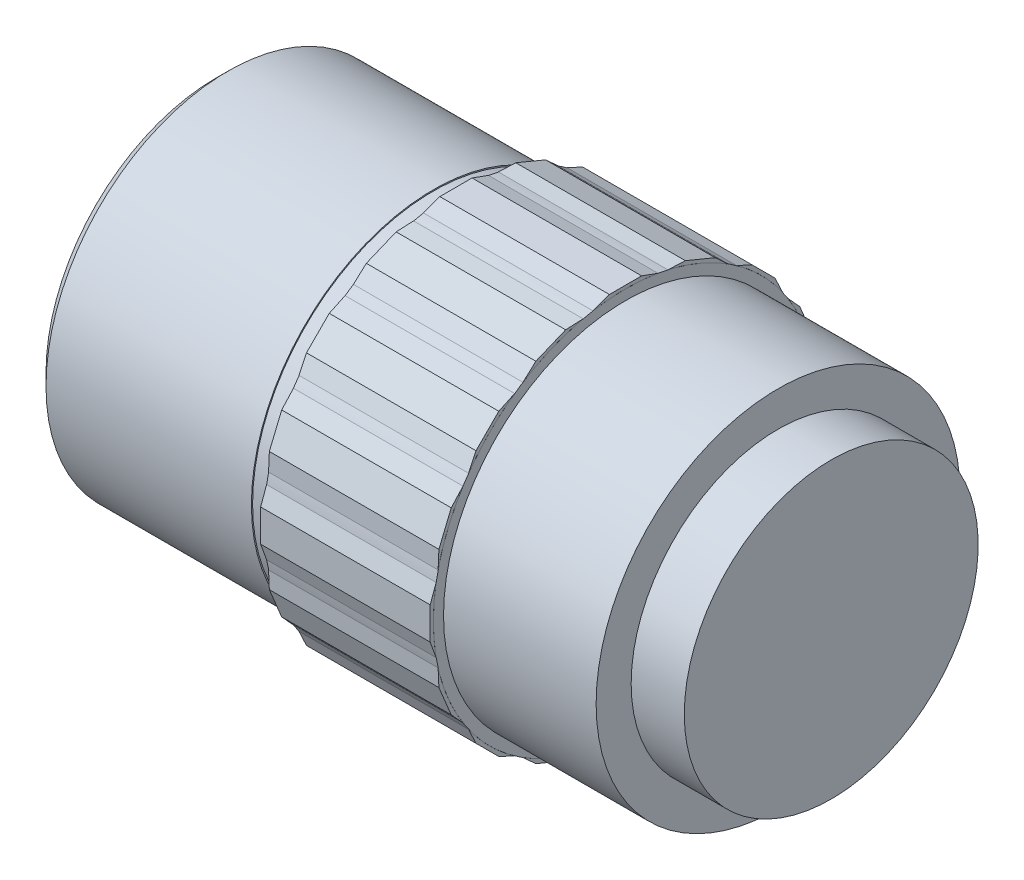
SolidWorks part; units mm, degrees
ref_plane "Front Plane" through (0, 0, 0) normal (0, 0, 1) x (1, 0, 0)
ref_plane "Top Plane" through (0, 0, 0) normal (0, 1, 0) x (1, 0, 0)
ref_plane "Right Plane" through (0, 0, 0) normal (1, 0, 0) x (0, 0, -1)
sketch "Sketch1" plane through (0, 0, 0) normal (0, 0, 1) x (1, 0, 0)
  line L0 (0, 0) -> (0, 13)
  line L1 (0, 13) -> (-4.7, 13)
  line L2 (-4.7, 13) -> (-4.7, 16.1)
  line L3 (-4.7, 16.1) -> (-18.2, 16.1)
  line L4 (-18.2, 16.1) -> (-18.2, 17)
  line L5 (-18.2, 17) -> (-33.2, 17)
  line L6 (-33.2, 17) -> (-33.2, 16.1)
  line L7 (-33.2, 16.1) -> (-53.3705, 16.1)
  line L8 (-53.3705, 16.1) -> (-54.4, 15.0705)
  line L9 (-54.4, 15.0705) -> (-54.4, 7.8723)
  line L10 (-54.4, 7.8723) -> (-54.7, 7.5723)
  line L11 (-54.7, 7.5723) -> (-54.7, 0)
  line L12 (-54.7, 0) -> (0, 0)
  point P8 (-18.2, 16.55)
  point P15 (-53.8057, 8.9982)
  point P16 (-53.664, 14.7558)
  point P17 (-53.9774, 16.1)
  dimension "D1" = 4.7
  dimension "D2" = 13.5
  dimension "D3" = 15
  dimension "D4" = 50
  dimension "D5" = 16.1
  dimension "D6" = 45
  dimension "D7" = 45
  dimension "D8" = 17
  dimension "D9" = 13
revolve "Revolve1" add sketch "Sketch1" angle 360 about L12
sketch "Sketch2" plane through (-33.2, 0, 0) normal (-1, 0, 0) x (0, 0, 1)
  line L0 (16.7543, 2.8797) -> (17.2804, 1.4257)
  line L1 (17.2804, 1.4257) -> (17.2804, -1.4257)
  line L2 (17.2804, -1.4257) -> (16.7543, -2.8797)
  line L3 (15.4194, -7.9301) -> (14.377, -9.0721)
  line L4 (16.5106, -5.2957) -> (15.4194, -7.9301)
  line L5 (16.581, -3.7511) -> (16.5106, -5.2957)
  line L6 (11.2109, -13.2272) -> (9.8108, -13.8833)
  line L7 (13.2272, -11.2109) -> (11.2109, -13.2272)
  line L8 (13.8833, -9.8108) -> (13.2272, -11.2109)
  line L9 (5.2957, -16.5106) -> (3.7511, -16.581)
  line L10 (7.9301, -15.4194) -> (5.2957, -16.5106)
  line L11 (9.0721, -14.377) -> (7.9301, -15.4194)
  line L12 (-1.4257, -17.2804) -> (-2.8797, -16.7543)
  line L13 (1.4257, -17.2804) -> (-1.4257, -17.2804)
  line L14 (2.8797, -16.7543) -> (1.4257, -17.2804)
  line L15 (-7.9301, -15.4194) -> (-9.0721, -14.377)
  line L16 (-5.2957, -16.5106) -> (-7.9301, -15.4194)
  line L17 (-3.7511, -16.581) -> (-5.2957, -16.5106)
  line L18 (-13.2272, -11.2109) -> (-13.8833, -9.8108)
  line L19 (-11.2109, -13.2272) -> (-13.2272, -11.2109)
  line L20 (-9.8108, -13.8833) -> (-11.2109, -13.2272)
  line L21 (-16.5106, -5.2957) -> (-16.581, -3.7511)
  line L22 (-15.4194, -7.9301) -> (-16.5106, -5.2957)
  line L23 (-14.377, -9.0721) -> (-15.4194, -7.9301)
  line L24 (-17.2804, 1.4257) -> (-16.7543, 2.8797)
  line L25 (-17.2804, -1.4257) -> (-17.2804, 1.4257)
  line L26 (-16.7543, -2.8797) -> (-17.2804, -1.4257)
  line L27 (-15.4194, 7.9301) -> (-14.377, 9.0721)
  line L28 (-16.5106, 5.2957) -> (-15.4194, 7.9301)
  line L29 (-16.581, 3.7511) -> (-16.5106, 5.2957)
  line L30 (-11.2109, 13.2272) -> (-9.8108, 13.8833)
  line L31 (-13.2272, 11.2109) -> (-11.2109, 13.2272)
  line L32 (-13.8833, 9.8108) -> (-13.2272, 11.2109)
  line L33 (-5.2957, 16.5106) -> (-3.7511, 16.581)
  line L34 (-7.9301, 15.4194) -> (-5.2957, 16.5106)
  line L35 (-9.0721, 14.377) -> (-7.9301, 15.4194)
  line L36 (1.4257, 17.2804) -> (2.8797, 16.7543)
  line L37 (-1.4257, 17.2804) -> (1.4257, 17.2804)
  line L38 (-2.8797, 16.7543) -> (-1.4257, 17.2804)
  line L39 (7.9301, 15.4194) -> (9.0721, 14.377)
  line L40 (5.2957, 16.5106) -> (7.9301, 15.4194)
  line L41 (3.7511, 16.581) -> (5.2957, 16.5106)
  line L42 (13.2272, 11.2109) -> (13.8833, 9.8108)
  line L43 (11.2109, 13.2272) -> (13.2272, 11.2109)
  line L44 (9.8108, 13.8833) -> (11.2109, 13.2272)
  line L45 (16.5106, 5.2957) -> (16.581, 3.7511)
  line L46 (15.4194, 7.9301) -> (16.5106, 5.2957)
  line L47 (14.377, 9.0721) -> (15.4194, 7.9301)
  circle A0 centre (0, 0) radius 17 construction
  circle A1 centre (0, 0) radius 17
  point P4 (17.2804, 0)
  circle M4 centre (0, 0) radius 17
  dimension "D1" = 16
extrude "Boss-Extrude1" add sketch "Sketch2" against normal blind 15 separate body contours L2 L1 L0 M4 | L5 L3 L4 M4 | L8 L6 L7 M4 | L11 L9 L10 M4 | L14 L12 L13 M4 | L17 L15 L16 M4 | L20 L18 L19 M4 | L23 L21 L22 M4 | L26 L24 L25 M4 | L29 L27 L28 M4 | L32 L30 L31 M4 | L35 L33 L34 M4 | L38 L36 L37 M4 | L41 L39 L40 M4 | L44 L42 L43 M4 | L47 L45 L46 M4
sketch "Sketch3" plane through (-33.2, 0, 0) normal (-1, 0, 0) x (0, 0, 1)
  circle A1 centre (0, 0) radius 17
  circle A2 centre (0, 0) radius 17
  circle A3 centre (0, 0) radius 16.1
  circle A4 centre (0, 0) radius 15.9936
  circle M2 centre (0, 0) radius 16.1
  dimension "D1" = 0
extrude "Cut-Extrude1" cut sketch "Sketch3" along normal blind 2 contours A4 M2
